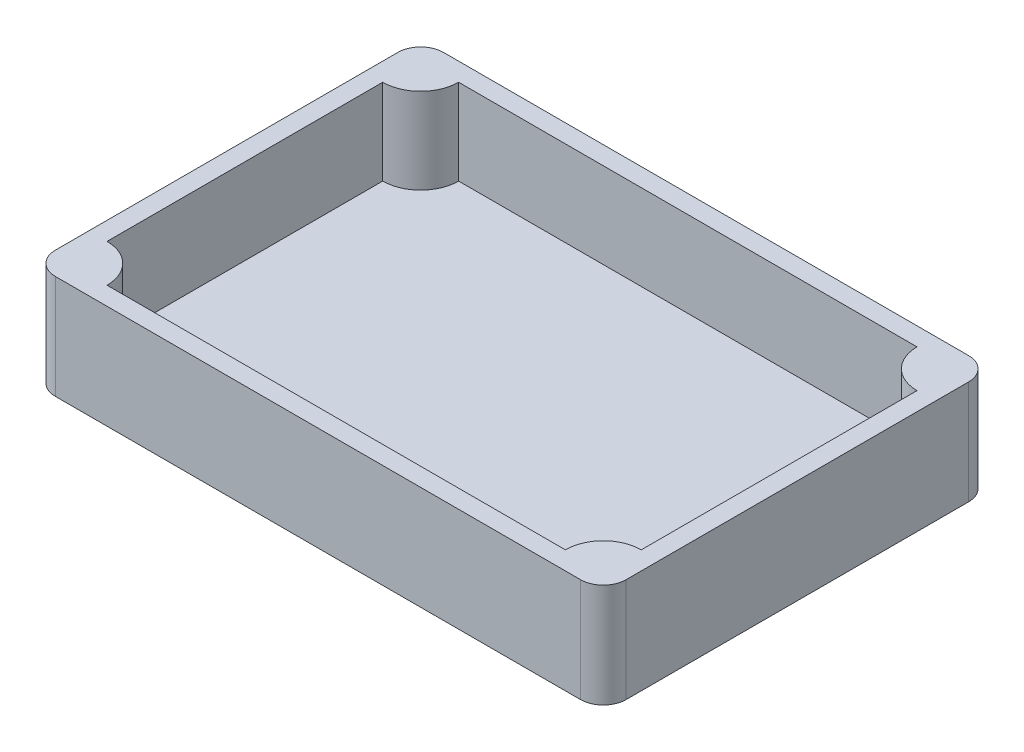
SolidWorks part; units mm, degrees
ref_plane "Front Plane" through (0, 0, 0) normal (0, 0, 1) x (1, 0, 0)
ref_plane "Top Plane" through (0, 0, 0) normal (0, 1, 0) x (1, 0, 0)
ref_plane "Right Plane" through (0, 0, 0) normal (1, 0, 0) x (0, 0, -1)
sketch "Sketch1" plane through (0, 0, 0) normal (0, 1, 0) x (1, 0, 0)
  line L1 (-46, -34) -> (46, -34)
  line L2 (-50, -30) -> (-50, 30)
  line L3 (-46, 34) -> (46, 34)
  line L4 (50, -30) -> (50, 30)
  line L5 (-50, -34) -> (50, 34) construction
  line L6 (-50, 34) -> (50, -34) construction
  arc A0 (-46, -34) -> (-50, -30) centre (-46, -30) cw
  arc A1 (46, -34) -> (50, -30) centre (46, -30) ccw
  arc A2 (46, 34) -> (50, 30) centre (46, 30) cw
  arc A3 (-50, 30) -> (-46, 34) centre (-46, 30) cw
  point P0 (0, 0)
  dimension "D3" = 4
  dimension "D1" = 100
  dimension "D2" = 68
extrude "Boss-Extrude1" add sketch "Sketch1" along normal blind 3.2
sketch "Sketch2" plane through (0, 3.2, 0) normal (0, 1, 0) x (1, 0, 0)
  line L0 (-40.8696, 27.7913) -> (40.8696, -27.7913) construction
  line L1 (-46, -34) -> (46, -34)
  line L2 (-50, -27.196) -> (-50, 30)
  line L3 (-46, 34) -> (46, 34)
  line L4 (50, -30) -> (50, 30)
  line L5 (-48.5946, -33.0443) -> (-45.2941, -30.8) construction
  line L6 (-50, 34) -> (-48.5946, 33.0443) construction
  line L7 (-46.8, -30.8) -> (-45.2941, -30.8)
  line L8 (-46.8, -24.15) -> (-46.8, 24.15)
  line L10 (46.8, -24.15) -> (46.8, 24.1669)
  line L11 (-41.2451, -27.1442) -> (41.2592, 27.1535) construction
  line L12 (-41.2451, 27.1442) -> (41.2451, -27.1442) construction
  line L13 (-40.15, 30.8) -> (40.1669, 30.8)
  line L14 (48.5946, -33.0443) -> (50, -34) construction
  line L15 (48.5946, 33.0443) -> (50, 34) construction
  line L16 (-40.8696, -27.7913) -> (40.8837, 27.8009) construction
  line L17 (-40.15, -30.8) -> (40.15, -30.8)
  arc A0 (-46, -34) -> (-50, -30) centre (-46, -30) cw
  arc A1 (46, -34) -> (50, -30) centre (46, -30) ccw
  arc A2 (46, 34) -> (50, 30) centre (46, 30) cw
  arc A3 (-50, 30) -> (-46, 34) centre (-46, 30) cw
  arc A5 (-46.8, 24.15) -> (-40.15, 30.8) centre (-46.8, 30.8) ccw
  arc A6 (40.1669, 30.8) -> (46.8, 24.1669) centre (46.8, 30.8) ccw
  arc A7 (46.8, -24.15) -> (40.15, -30.8) centre (46.8, -30.8) ccw
  arc A8 (-40.15, -30.8) -> (-46.8, -24.15) centre (-46.8, -30.8) ccw
  point P0 (0, 0)
  point P18 (0, 0)
  dimension "D3" = 4
  dimension "D6" = 13.2661
  dimension "D1" = 100
  dimension "D4" = 93.6
  dimension "D5" = 61.6
extrude "Boss-Extrude2" add sketch "Sketch2" along normal blind 15
